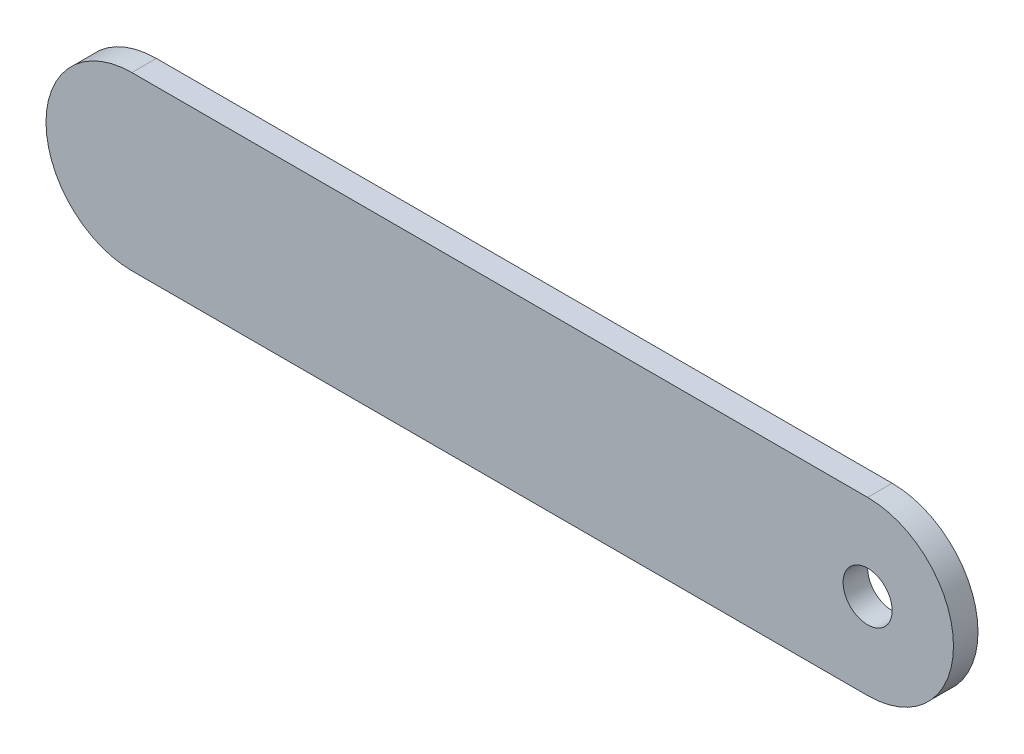
SolidWorks part; units mm, degrees
ref_plane "Front Plane" through (0, 0, 0) normal (0, 0, 1) x (1, 0, 0)
ref_plane "Top Plane" through (0, 0, 0) normal (0, 1, 0) x (1, 0, 0)
ref_plane "Right Plane" through (0, 0, 0) normal (1, 0, 0) x (0, 0, -1)
sketch "Sketch1" plane through (0, 0, 0) normal (0, 0, 1) x (1, 0, 0)
  line L0 (-43.8574, 7) -> (16.1426, 7)
  line L1 (-43.8574, -7) -> (16.1426, -7)
  circle A0 centre (16.1426, 0) radius 2
  arc A1 (16.1426, -7) -> (16.1426, 7) centre (16.1426, 0) ccw
  arc A2 (-43.8574, 7) -> (-43.8574, -7) centre (-43.8574, 0) ccw
  dimension "D1" = 4
  dimension "D2" = 7
  dimension "D3" = 7
  dimension "D4" = 60
extrude "Boss-Extrude1" add sketch "Sketch1" along normal blind 2
